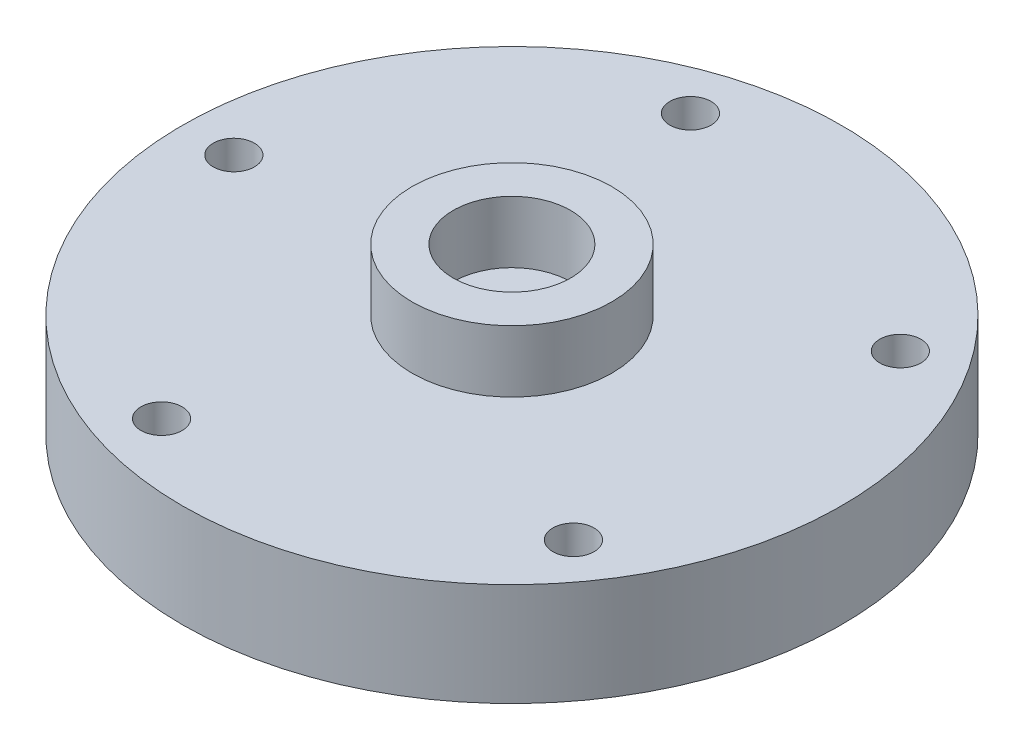
SolidWorks part; units mm, degrees
ref_plane "Front Plane" through (0, 0, 0) normal (0, 0, 1) x (1, 0, 0)
ref_plane "Top Plane" through (0, 0, 0) normal (0, 1, 0) x (1, 0, 0)
ref_plane "Right Plane" through (0, 0, 0) normal (1, 0, 0) x (0, 0, -1)
sketch "Sketch1" plane through (0, 0, 0) normal (0, 1, 0) x (1, 0, 0)
  line L0 (-13.5, 0) -> (13.5, 0) construction
  circle A0 centre (0, 0) radius 16
  circle A1 centre (0, 0) radius 13.5
  circle A2 centre (0, 0) radius 1
  circle A3 centre (-13.5, 0) radius 1
  circle A4 centre (-4.1717, 12.8393) radius 1
  circle A5 centre (10.9217, 7.9351) radius 1
  circle A6 centre (10.9217, -7.9351) radius 1
  circle A7 centre (-4.1717, -12.8393) radius 1
  point P19 (0, 0)
  dimension "D1" = 32
  dimension "D2" = 2.5
  dimension "D3" = 2
  dimension "D4" = 2
  dimension "D5" = 5
extrude "Boss-Extrude1" add sketch "Sketch1" along normal blind 2 and the other way blind 3 contours A0 A7 A1 A3 A4 A5 A6 | L0 A3 A1 A7 A6 A2 | A3 L0 A2 A1 A5 A4
sketch "Sketch2" plane through (0, 2, 0) normal (0, 1, 0) x (1, 0, 0)
  circle A0 centre (0, 0) radius 2.85
  circle A1 centre (0, 0) radius 4.85
  dimension "D1" = 5.7
  dimension "D2" = 2
extrude "Boss-Extrude3" add sketch "Sketch2" along normal blind 3 contours A1 A0
sketch "Sketch4" plane through (0, 2, 0) normal (0, 1, 0) x (1, 0, 0)
  circle A0 centre (0, 0) radius 2
sketch "Sketch5" plane through (0, -3, 0) normal (0, -1, 0) x (1, 0, 0)
  circle A0 centre (0, 0) radius 2
extrude "Cut-Extrude2" cut sketch "Sketch5" against normal blind 1
